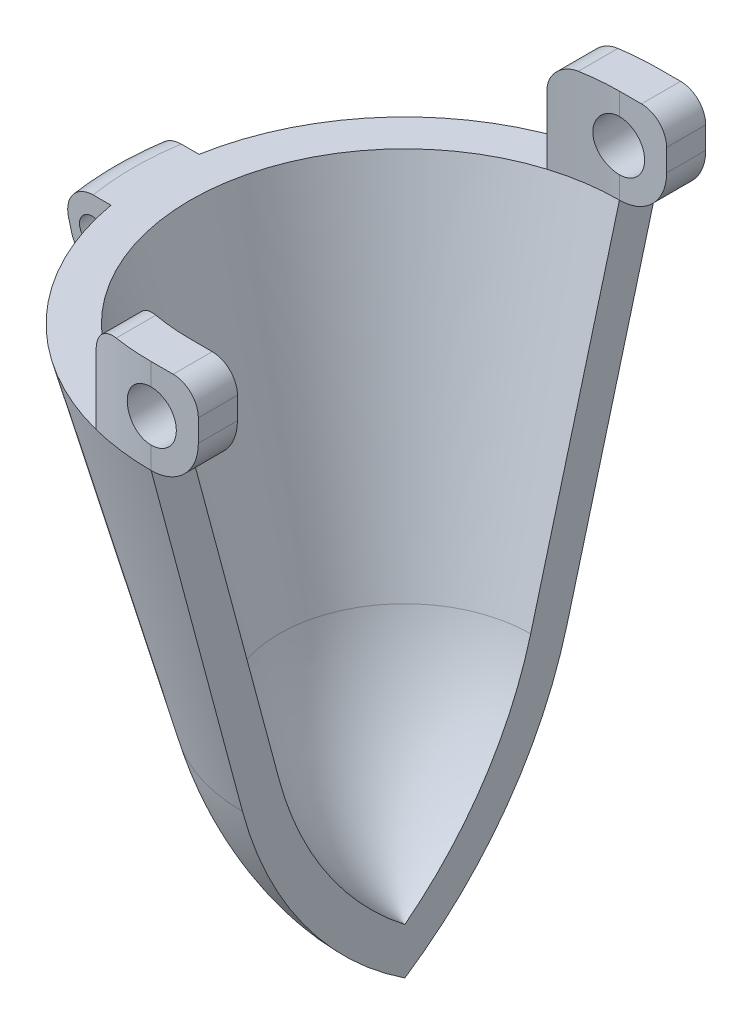
SolidWorks part; units mm, degrees
ref_plane "Alzado" through (0, 0, 0) normal (0, 0, 1) x (1, 0, 0)
ref_plane "Planta" through (0, 0, 0) normal (0, 1, 0) x (1, 0, 0)
ref_plane "Vista lateral" through (0, 0, 0) normal (1, 0, 0) x (0, 0, -1)
sketch "Croquis1" plane through (0, 0, 0) normal (1, 0, 0) x (0, 0, -1)
  line L1 (-25.7956, 35.8166) -> (-40.3139, 90)
  line L2 (-40.3139, 90) -> (-34.1023, 90)
  line L3 (-34.1023, 90) -> (-20, 37.3696)
  line L5 (0, 7.3696) -> (0, 0)
  line L6 (0, 0) -> (0, 62.8711) construction
  arc A0 (0, 0) -> (-25.7956, 35.8166) centre (34.3409, 51.9302) cw
  arc A1 (-20, 37.3696) -> (0, 7.3696) centre (34.3409, 51.9302) ccw
  dimension "D1" = 15
  dimension "D2" = 6
  dimension "D3" = 20
  dimension "D4" = 90
  dimension "D5" = 30
revolve "Revolución1" add sketch "Croquis1" angle 180 about L5
sketch "Croquis3" plane through (0, 90, 0) normal (0, 1, 0) x (1, 0, 0)
  line L0 (-10, -32.6032) -> (-10, -39.054)
  line L3 (-10, 32.6032) -> (-10, 39.054)
  line L4 (-46.5845, 0) -> (22.4461, 0) construction
  line L7 (0, -34.1023) -> (10, -34.1023)
  line L8 (10, -34.1023) -> (10, -40.3139)
  line L9 (10, -40.3139) -> (0, -40.3139)
  line L10 (10, 40.3139) -> (0, 40.3139)
  line L11 (10, 34.1023) -> (10, 40.3139)
  line L12 (0, 34.1023) -> (10, 34.1023)
  arc A0 (-10, -32.6032) -> (0, -34.1023) centre (0, 0) ccw
  arc A1 (0, 34.1023) -> (0, -34.1023) centre (0, 0) ccw construction
  arc A2 (-10, -39.054) -> (0, -40.3139) centre (0, 0) ccw
  arc A3 (0, 40.3139) -> (0, -40.3139) centre (0, 0) ccw construction
  arc A6 (-10, 32.6032) -> (0, 34.1023) centre (0, 0) cw
  arc A7 (-10, 39.054) -> (0, 40.3139) centre (0, 0) cw
  dimension "D1" = 6.2117
  dimension "D2" = 10
  dimension "D3" = 10
extrude "Saliente-Extruir1" add sketch "Croquis3" along normal blind 15
ref_plane "Plano1" through (0, 0, 40.3139) normal (0, 0, 1) x (1, 0, 0)
sketch "Croquis4" plane through (0, 0, 40.3139) normal (0, 0, 1) x (1, 0, 0)
  line L2 (-10, 90) -> (0, 90) construction
  line L4 (-10, 105) -> (-10, 90) construction
  circle A0 centre (0, 97.5) radius 4
  dimension "D1" = 8
  dimension "D2" = 7.5
  dimension "D3" = 10
extrude "Cortar-Extruir1" cut sketch "Croquis4" against normal through all
sketch "Croquis5" plane through (0, 0, 0) normal (0, 0, 1) x (1, 0, 0)
  line L0 (-40.3139, 90) -> (-48.3139, 90)
  line L1 (-48.3139, 90) -> (-45.6345, 80)
  line L2 (-45.6345, 80) -> (-37.6345, 80)
  line L3 (-40.3139, 90) -> (-25.7956, 35.8166) construction
  line L4 (-37.6345, 80) -> (-40.3139, 90)
  line L5 (0, 0) -> (0, 21.2258) construction
  line L6 (0, 0) -> (0, 35.8166) construction
  dimension "D1" = 8
  dimension "D2" = 10
revolve "Revolución2" add sketch "Croquis5" angle 10 about L5 other way angle 10
sketch "Croquis6" plane through (0, 90, 0) normal (0, 1, 0) x (1, 0, 0)
  line L0 (-39.7015, 7.0004) -> (-47.8041, 7.0004)
  line L1 (-47.8041, 7.0004) -> (-47.5799, 8.3896)
  line L2 (-47.5799, 8.3896) -> (-39.7015, 7.0004)
  line L3 (-39.7015, -7.0004) -> (-47.8041, -7.0004)
  line L4 (-47.8041, -7.0004) -> (-47.5799, -8.3896)
  line L5 (-47.5799, -8.3896) -> (-39.7015, -7.0004)
  arc A0 (-47.5799, 8.3896) -> (-47.5799, -8.3896) centre (0, 0) ccw construction
extrude "Cortar-Extruir2" cut sketch "Croquis6" against normal blind 10
sketch "Croquis7" plane through (0, 0, 7.0004) normal (0, 0, 1) x (1, 0, 0)
  line L0 (-39.7015, 80) -> (-45.0943, 80) construction
  circle A0 centre (-42.7015, 85) radius 2
  dimension "D3" = 4
  dimension "D1" = 5
  dimension "D2" = 3
extrude "Cortar-Extruir3" cut sketch "Croquis7" against normal through all
sketch "Croquis8" plane through (0, 0, 40.3139) normal (0, 0, 1) x (1, 0, 0)
  line L2 (7.5, 97.5) -> (7.5, 105)
  line L3 (0, 105) -> (10, 105) construction
  line L4 (7.5, 105) -> (10, 105)
  line L5 (10, 105) -> (10, 90)
  line L6 (10, 90) -> (0, 90)
  arc A0 (0, 90) -> (7.5, 97.5) centre (0, 97.5) ccw
extrude "Cortar-Extruir4" cut sketch "Croquis8" against normal through all
fillet "Redondeo1" radius 4 6 edges at (7.5, 105, -37.2081) (7.5, 105, 37.2081) (-10, 105, -35.8286) (-10, 105, 35.8286) (-45.6345, 80, 0)
